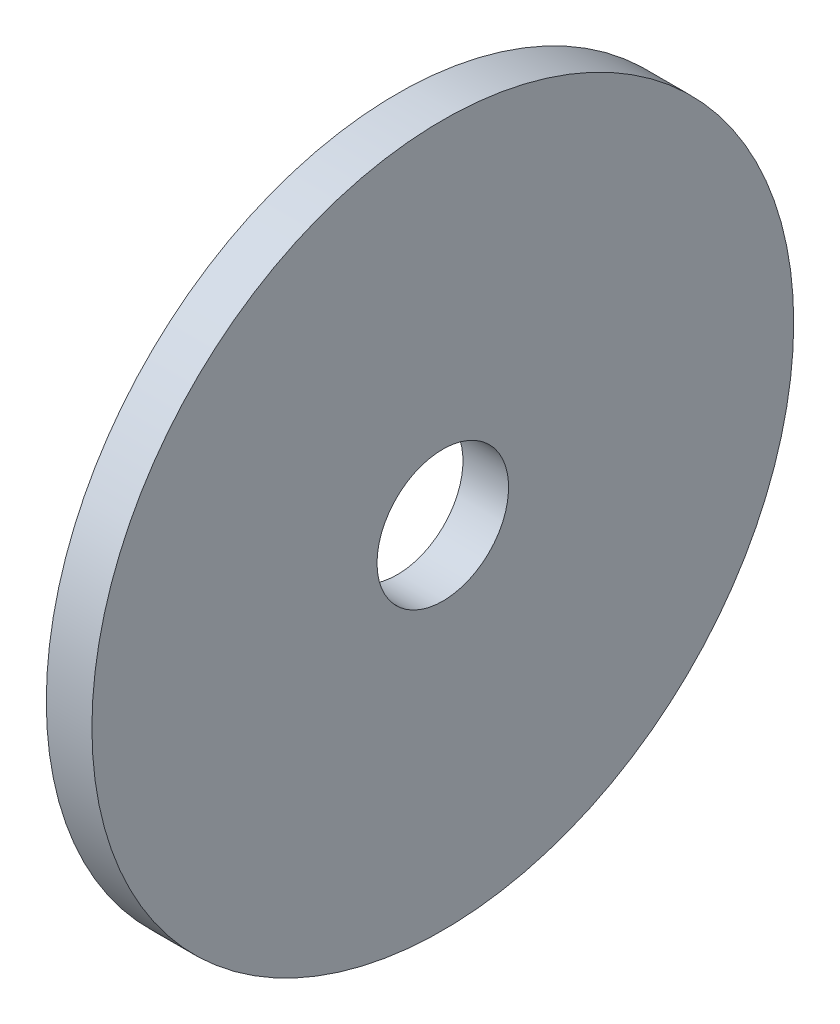
SolidWorks part; units mm, degrees
ref_plane "Front Plane" through (0, 0, 0) normal (0, 0, 1) x (1, 0, 0)
ref_plane "Top Plane" through (0, 0, 0) normal (0, 1, 0) x (1, 0, 0)
ref_plane "Right Plane" through (0, 0, 0) normal (1, 0, 0) x (0, 0, -1)
sketch "Sketch1" plane through (0, 0, 0) normal (1, 0, 0) x (0, 0, -1)
  circle A0 centre (0, 0) radius 12.7
  circle A1 centre (0, 0) radius 2.3813
  dimension "OD" = 25.4
  dimension "ID" = 4.7625
extrude "Boss-Extrude1" add sketch "Sketch1" along normal blind 1.651
